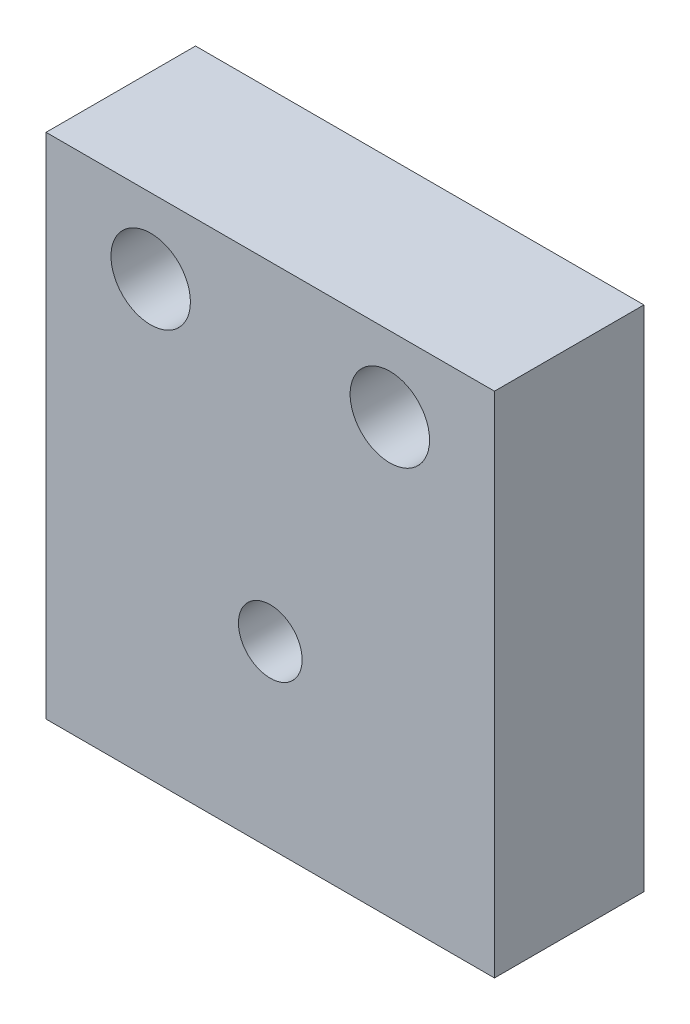
SolidWorks part; units mm, degrees
material "6063-T5"
ref_plane "Front Plane" through (0, 0, 0) normal (0, 0, 1) x (1, 0, 0)
ref_plane "Top Plane" through (0, 0, 0) normal (0, 1, 0) x (1, 0, 0)
ref_plane "Right Plane" through (0, 0, 0) normal (1, 0, 0) x (0, 0, -1)
sketch "Sketch1" plane through (0, 0, 0) normal (0, 0, 1) x (1, 0, 0)
  line L1 (0, 0) -> (38.1, 0)
  line L2 (0, 0) -> (0, 43.18)
  line L3 (0, 43.18) -> (38.1, 43.18)
  line L4 (38.1, 0) -> (38.1, 43.18)
  dimension "D1" = 38.1
  dimension "D2" = 43.18
extrude "Boss-Extrude1" add sketch "Sketch1" against normal blind 12.7
sketch "Sketch3" plane through (0, 0, 0) normal (0, 0, 1) x (1, 0, 0)
  line L0 (19.05, -987.2485) -> (19.05, 49012.7515) construction
  line L1 (0, 43.18) -> (0, 0) construction
  line L2 (38.1, 0) -> (38.1, 43.18) construction
  line L3 (38.1, 43.18) -> (0, 43.18) construction
  point P6 (19.05, 15.24)
  dimension "D1" = 27.94
sketch "Sketch5" plane through (0, 0, 0) normal (0, 0, 1) x (1, 0, 0)
  line L0 (19.05, -968.1712) -> (19.05, 49031.8288) construction
  line L1 (0, 43.18) -> (0, 0) construction
  line L2 (38.1, 0) -> (38.1, 43.18) construction
  line L3 (38.1, 43.18) -> (0, 43.18) construction
  point P6 (8.89, 36.83)
  point P7 (29.21, 36.83)
  dimension "D1" = 20.32
  dimension "D2" = 6.35
hole_wizard "17/64 (0.26563) Diameter Hole1" positions "3DSketch2" profile "Sketch7" hole size "17/64" standard "ANSI Inch" end condition through all
sketch3d "3DSketch2"
  point P0 (29.21, 36.83, 0)
  point P3 (8.89, 36.83, 0)
sketch "Sketch7" plane through (29.21, 36.83, 0) normal (1, 0, 0) x (0, -1, 0)
  line L0 (0, 0) -> (0, 12.7)
  line L1 (0, 12.7) -> (3.3735, 12.7)
  line L2 (3.3735, 12.7) -> (3.3735, 0)
  line L5 (3.3735, 0) -> (0, 0)
  line L11 (0, -6.35) -> (0, 107.95) construction
  dimension "Thru Hole Dia." = 6.747
  dimension "Thru Hole Depth" = 12.7
sketch "Sketch11" plane through (0, 0, 0) normal (-1, 0, 0) x (0, 0, 1)
  line L0 (-6.35, -976.0873) -> (-6.35, 49023.9127) construction
  line L1 (-12.7, 43.18) -> (-12.7, 0) construction
  line L2 (0, -200968.1712) -> (0, 249031.8288) construction
  line L3 (-12.7, 43.18) -> (0, 43.18) construction
  point P6 (-6.35, 27.94)
  dimension "D1" = 15.24
hole_wizard "1/4-20 Tapped Hole2" positions "3DSketch4" profile "Sketch12" tap size "1/4-20" standard "ANSI Inch"
sketch3d "3DSketch4"
  point P0 (0, 27.94, -6.35)
sketch "Sketch12" plane through (0, 27.94, -6.35) normal (0, 1, 0) x (0, 0, 1)
  line L0 (0, 0) -> (0, 14.2338)
  line L1 (0, 14.2338) -> (2.5527, 12.7)
  line L2 (2.5527, 12.7) -> (2.5527, 0)
  line L5 (2.5527, 0) -> (0, 0)
  line L10 (0, 14.2338) -> (-2.5527, 12.7) construction
  line L11 (0, -6.35) -> (0, 107.95) construction
  dimension "Tap Drill Dia." = 5.1054
  dimension "Tap Drill Depth" = 12.7
  dimension "Drill Angle" = 118
cosmetic thread "Hole Thread2" parameters "D1"=10.16, "D2"=6.35
hole_wizard "1/4-28 Tapped Hole1" positions "3DSketch5" profile "Sketch13" tap size "1/4-28" standard "ANSI Inch" end condition through all
sketch3d "3DSketch5"
  point P0 (19.05, 15.24, 0)
sketch "Sketch13" plane through (19.05, 15.24, 0) normal (1, 0, 0) x (0, -1, 0)
  line L0 (0, 0) -> (0, 12.7)
  line L1 (0, 12.7) -> (2.7051, 12.7)
  line L2 (2.7051, 12.7) -> (2.7051, 0)
  line L5 (2.7051, 0) -> (0, 0)
  line L11 (0, -6.35) -> (0, 107.95) construction
  dimension "Thru Tap Drill Dia." = 5.4102
  dimension "Thru Tap Drill Depth" = 12.7
cosmetic thread "Hole Thread3" parameters "D2"=6.35
